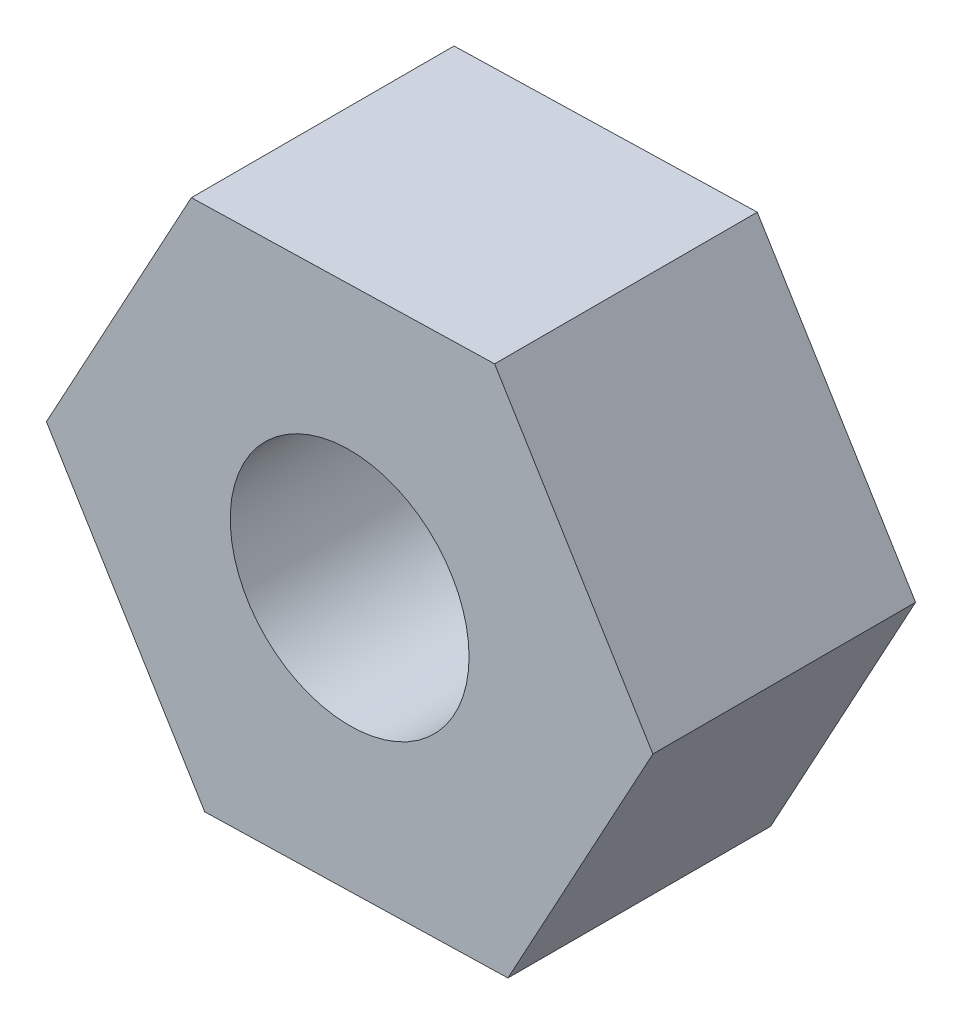
SolidWorks part; units mm, degrees
ref_plane "Alzado" through (0, 0, 0) normal (0, 0, 1) x (1, 0, 0)
ref_plane "Planta" through (0, 0, 0) normal (0, 1, 0) x (1, 0, 0)
ref_plane "Vista lateral" through (0, 0, 0) normal (1, 0, 0) x (0, 0, -1)
sketch "Croquis1" plane through (0, 0, 0) normal (0, 0, 1) x (1, 0, 0)
  line L1 (3.3142, -5.4175) -> (6.3488, 0.1615)
  line L2 (6.3488, 0.1615) -> (3.0346, 5.579)
  line L3 (3.0346, 5.579) -> (-3.3142, 5.4175)
  line L4 (-3.3142, 5.4175) -> (-6.3488, -0.1615)
  line L5 (-6.3488, -0.1615) -> (-3.0346, -5.579)
  line L6 (-3.0346, -5.579) -> (3.3142, -5.4175)
  circle A0 centre (0, 0) radius 5.5 construction
  circle A1 centre (0, 0) radius 2.5
  dimension "D1" = 11
extrude "Saliente-Extruir1" add sketch "Croquis1" along normal blind 5.5
